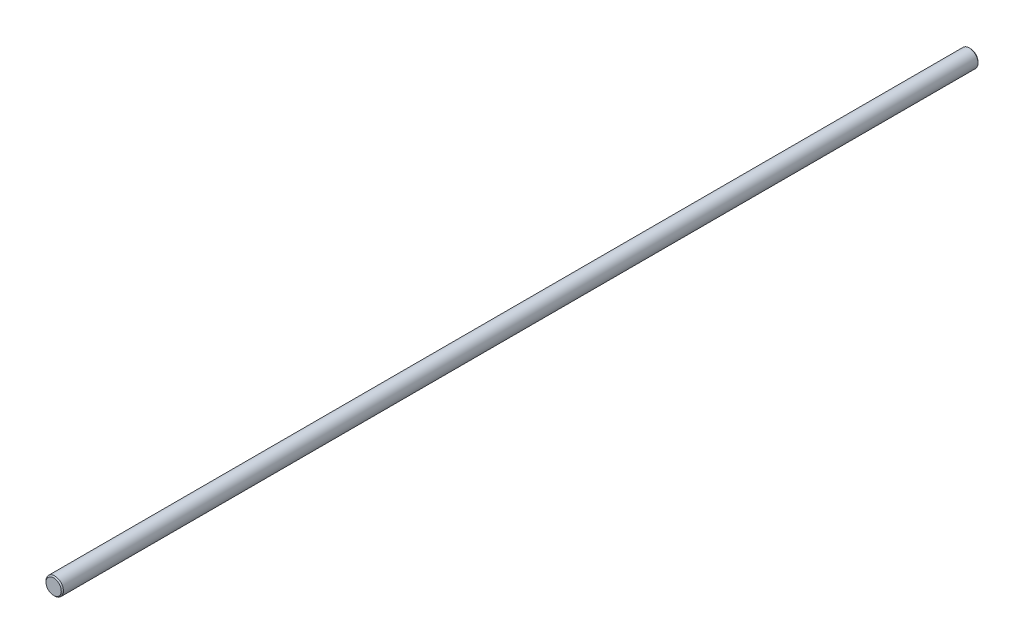
SolidWorks part; units mm, degrees
ref_plane "Płaszczyzna przednia" through (0, 0, 0) normal (0, 0, 1) x (1, 0, 0)
ref_plane "Płaszczyzna górna" through (0, 0, 0) normal (0, 1, 0) x (1, 0, 0)
ref_plane "Płaszczyzna prawa" through (0, 0, 0) normal (1, 0, 0) x (0, 0, -1)
sketch "Szkic1" plane through (0, 0, 0) normal (0, 0, 1) x (1, 0, 0)
  circle A0 centre (0, 0) radius 4
extrude "Dodanie-wyciągnięcie1" add sketch "Szkic1" along normal blind 420
chamfer "Sfazowanie1" distance 0.5 angle 45 2 edges at (4, 0, 420) (4, 0, 0)
